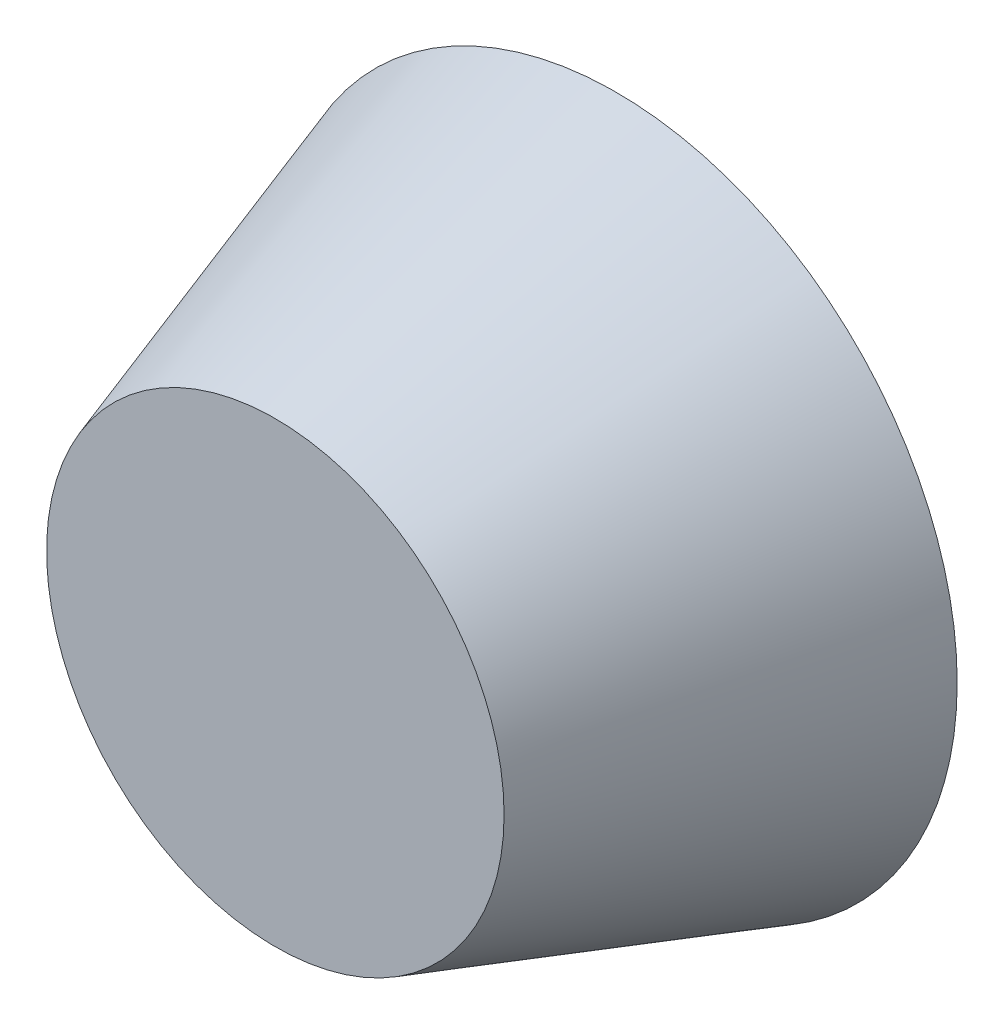
SolidWorks part; units mm, degrees
ref_plane "Front Plane" through (0, 0, 0) normal (0, 0, 1) x (1, 0, 0)
ref_plane "Top Plane" through (0, 0, 0) normal (0, 1, 0) x (1, 0, 0)
ref_plane "Right Plane" through (0, 0, 0) normal (1, 0, 0) x (0, 0, -1)
sketch "Sketch1" plane through (0, 0, 0) normal (0, 0, 1) x (1, 0, 0)
  circle A0 centre (0, 0) radius 5
ref_plane "Plane1" through (0, 0, 5) normal (0, 0, 1) x (1, 0, 0)
sketch "Sketch3" plane through (0, 0, 5) normal (0, 0, 1) x (1, 0, 0)
  circle A0 centre (0, 0) radius 3.3548
loft "Loft2" add profiles "Sketch1", "Sketch3"
